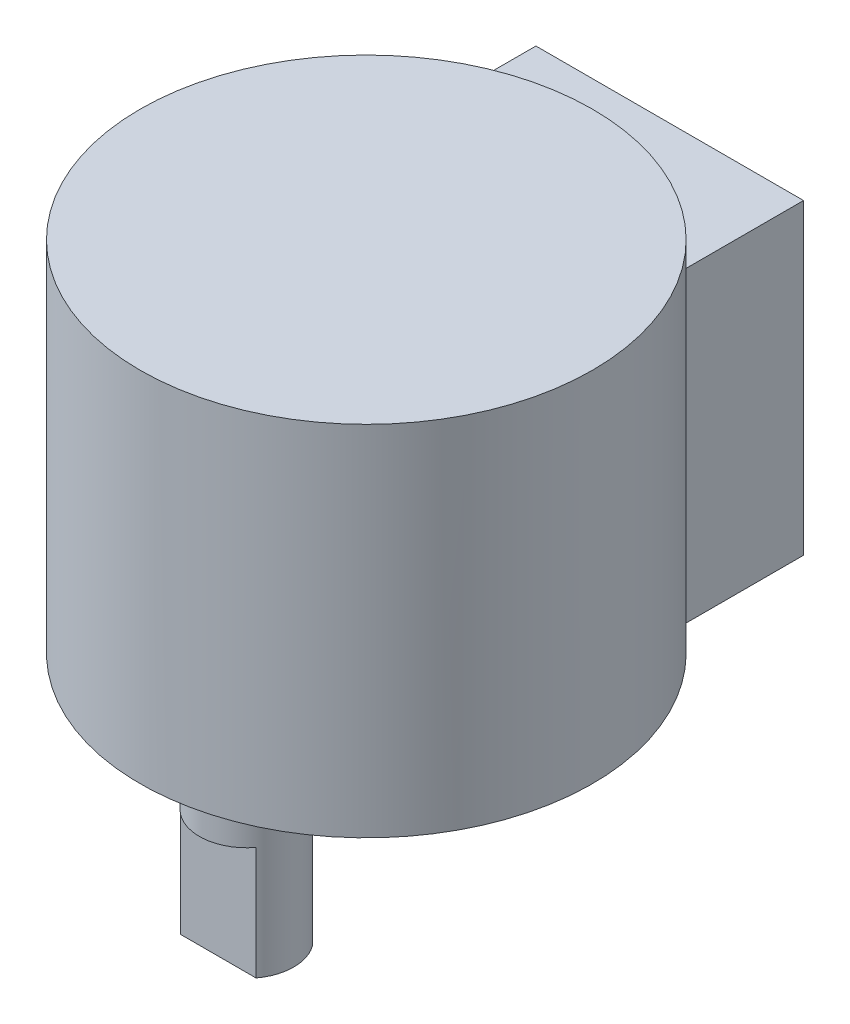
SolidWorks part; units mm, degrees
ref_plane "前视基准面" through (0, 0, 0) normal (0, 0, 1) x (1, 0, 0)
ref_plane "上视基准面" through (0, 0, 0) normal (0, 1, 0) x (1, 0, 0)
ref_plane "右视基准面" through (0, 0, 0) normal (1, 0, 0) x (0, 0, -1)
other "Configuration Table"
sketch "草图1" plane through (0, 0, 0) normal (0, 1, 0) x (1, 0, 0)
  circle A0 centre (0, 0) radius 12
  dimension "D1" = 24
extrude "凸台-拉伸1" add sketch "草图1" along normal blind 19
sketch "草图2" plane through (0, 0, 0) normal (0, -1, 0) x (1, 0, 0)
  line L1 (-7.1, -16.1) -> (7.1, -16.1)
  line L2 (-7.1, -16.1) -> (-7.1, -9.6742)
  line L3 (-7.1, -9.6742) -> (7.1, -9.6742)
  line L4 (7.1, -16.1) -> (7.1, -9.6742)
  line L5 (0, -9.6742) -> (0, -16.1) construction
  line L6 (-7.1, -12.8871) -> (7.1, -12.8871) construction
  circle A0 centre (0, 0) radius 12 construction
  point P0 (0, -12.8871)
  point P6 (0, 0)
  dimension "D1" = 14.2
  dimension "D2" = 16.1
extrude "凸台-拉伸2" add sketch "草图2" against normal blind 16.3
sketch "草图3" plane through (0, 0, 0) normal (0, -1, 0) x (1, 0, 0)
  circle A0 centre (0, 6.35) radius 3.5
  dimension "D2" = 7
  dimension "D1" = 6.35
extrude "凸台-拉伸3" add sketch "草图3" along normal blind 1
sketch "草图4" plane through (0, -1, 0) normal (0, -1, 0) x (1, 0, 0)
  circle A0 centre (0, 6.35) radius 2.5
  circle A1 centre (0, 6.35) radius 3.5 construction
  dimension "D1" = 5
extrude "凸台-拉伸4" add sketch "草图4" along normal blind 3
sketch "草图5" plane through (0, -4, 0) normal (0, -1, 0) x (1, 0, 0)
  line L0 (-2, 7.85) -> (2, 7.85)
  line L1 (-2, 4.85) -> (2, 4.85)
  arc A0 (-2, 7.85) -> (-2, 4.85) centre (0, 6.35) ccw
  circle A1 centre (0, 6.35) radius 2.5 construction
  arc A2 (2, 4.85) -> (2, 7.85) centre (0, 6.35) ccw
  point P8 (0, 0)
  dimension "D1" = 5
  dimension "D2" = 3
extrude "凸台-拉伸5" add sketch "草图5" along normal blind 6
sketch "草图6" plane through (0, 0, -16.1) normal (0, 0, -1) x (-1, 0, 0)
  line L0 (-7.1, 16.3) -> (-7.1, 0) construction
  line L1 (7.1, 0) -> (-7.1, 0) construction
  circle A0 centre (-3.6, 2.5) radius 0.7
  circle A1 centre (-2.1, 2.5) radius 0.7
  circle A2 centre (-0.6, 2.5) radius 0.7
  circle A3 centre (0.9, 2.5) radius 0.7
  circle A4 centre (2.4, 2.5) radius 0.7
  circle A5 centre (3.9, 2.5) radius 0.7
  dimension "D1" = 1.4
  dimension "D3" = 2.5
  dimension "D2" = 3.5
  dimension "D5" = 1.5
  dimension "D4" = 6
extrude "凸台-拉伸6" add sketch "草图6" along normal blind 2
